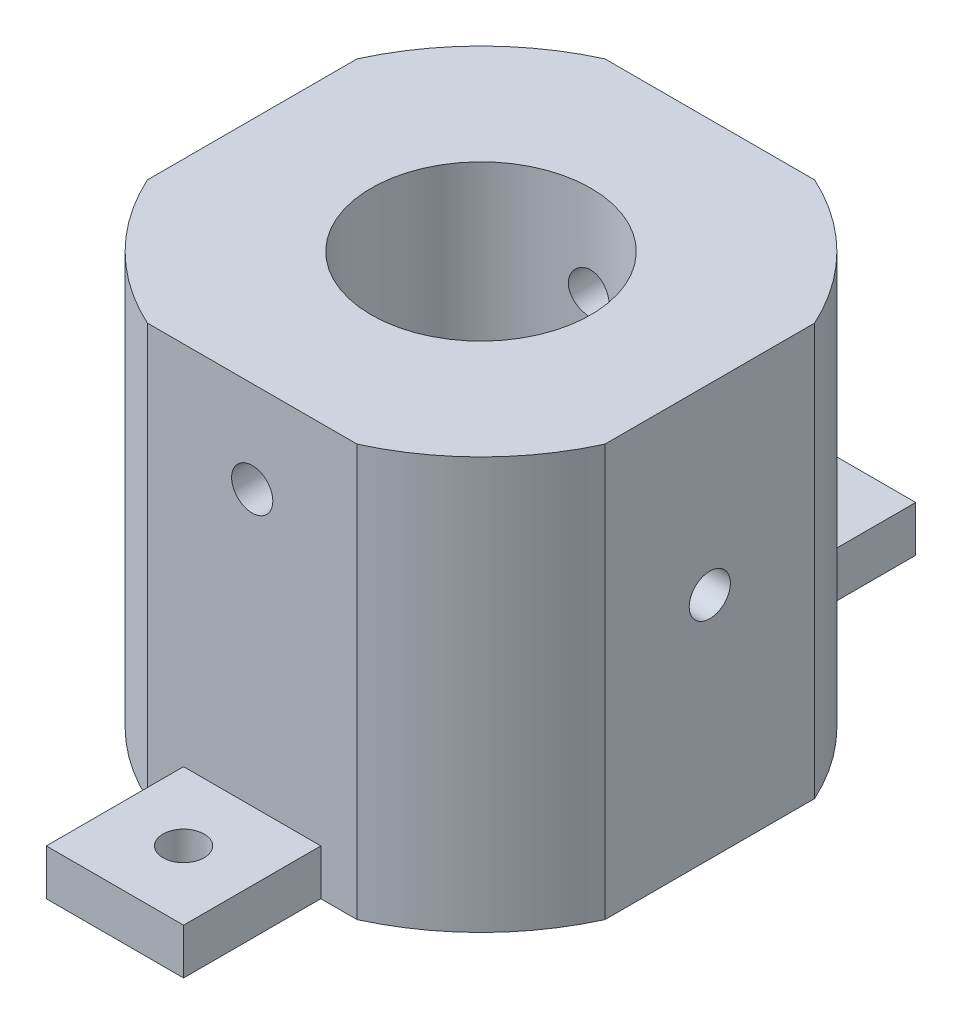
SolidWorks part; units mm, degrees
ref_plane "Ön Düzlem" through (0, 0, 0) normal (0, 0, 1) x (1, 0, 0)
ref_plane "Üst Düzlem" through (0, 0, 0) normal (0, 1, 0) x (1, 0, 0)
ref_plane "Sağ Düzlem" through (0, 0, 0) normal (1, 0, 0) x (0, 0, -1)
ref_plane "Plane1" through (0, 0, 0) normal (0, -1, 0) x (1, 0, 0)
sketch "Sketch1" plane through (0, 0, 0) normal (0, -1, 0) x (1, 0, 0)
  line L0 (-11.4564, -25) -> (11.4564, -25)
  line L1 (25, -11.4564) -> (25, 11.4564)
  line L2 (11.4564, 25) -> (-11.4564, 25)
  line L3 (-25, 11.4564) -> (-25, -11.4564)
  arc A0 (-25, -11.4564) -> (-11.4564, -25) centre (0, 0) ccw
  arc A1 (11.4564, -25) -> (25, -11.4564) centre (0, 0) ccw
  arc A2 (25, 11.4564) -> (11.4564, 25) centre (0, 0) ccw
  arc A3 (-11.4564, 25) -> (-25, 11.4564) centre (0, 0) ccw
extrude "Boss-Extrude1" add sketch "Sketch1" against normal blind 45
sketch "Sketch2" plane through (0, 0, -25) normal (0, 0, -1) x (-1, 0, 0)
  line L0 (-7.5, 5) -> (7.5, 5)
  line L1 (7.5, 5) -> (7.5, 0)
  line L2 (7.5, 0) -> (-7.5, 0)
  line L3 (-7.5, 0) -> (-7.5, 5)
extrude "Boss-Extrude2" add sketch "Sketch2" along normal blind 15
sketch "Sketch3" plane through (0, 0, 25) normal (0, 0, 1) x (1, 0, 0)
  line L0 (-7.5, 5) -> (7.5, 5)
  line L1 (7.5, 5) -> (7.5, 0)
  line L2 (7.5, 0) -> (-7.5, 0)
  line L3 (-7.5, 0) -> (-7.5, 5)
extrude "Boss-Extrude3" add sketch "Sketch3" along normal blind 15
hole_wizard "Ø24.0 (24) Diameter Hole1" positions "Sketch5" profile "Sketch4" hole size "Ø24.0" standard "ANSI Metric"
sketch "Sketch5" plane through (0, 0, 0) normal (0, -1, 0) x (-1, 0, 0)
  point P0 (0, 0)
sketch "Sketch4" plane through (0, 0, 0) normal (1, 0, 0) x (0, 0, -1)
  line L0 (0, 0) -> (0, 45)
  line L1 (0, 45) -> (12, 45)
  line L2 (12, 45) -> (12, 0)
  line L5 (12, 0) -> (0, 0)
  line L11 (0, -6.35) -> (0, 107.95) construction
  dimension "Thru Hole Dia." = 24
  dimension "Thru Hole Depth" = 45
hole_wizard "Ø4.5 (4.5) Diameter Hole1" positions "Sketch7" profile "Sketch6" hole size "Ø4.5" standard "ANSI Metric"
sketch "Sketch7" plane through (0, 0, -25) normal (0, 0, -1) x (-1, 0, 0)
  point P0 (0, 35)
sketch "Sketch6" plane through (0, 35, -25) normal (1, 0, 0) x (0, 1, 0)
  line L0 (0, 0) -> (0, 63.2128)
  line L1 (0, 63.2128) -> (2.25, 63.2128)
  line L2 (2.25, 63.2128) -> (2.25, 0)
  line L5 (2.25, 0) -> (0, 0)
  line L10 (0, 63.2128) -> (-2.25, 63.2128) construction
  line L11 (0, -6.35) -> (0, 107.95) construction
  dimension "Hole Dia." = 4.5
  dimension "Hole Depth" = 63.2128
  dimension "Drill Angle" = 180
hole_wizard "Ø4.5 (4.5) Diameter Hole2" positions "Sketch9" profile "Sketch8" hole size "Ø4.5" standard "ANSI Metric"
sketch "Sketch9" plane through (-25, 0, 0) normal (-1, 0, 0) x (0, 0, 1)
  point P0 (0, 25)
sketch "Sketch8" plane through (-25, 25, 0) normal (0, 1, 0) x (0, 0, 1)
  line L0 (0, 0) -> (0, 63.2128)
  line L1 (0, 63.2128) -> (2.25, 63.2128)
  line L2 (2.25, 63.2128) -> (2.25, 0)
  line L5 (2.25, 0) -> (0, 0)
  line L10 (0, 63.2128) -> (-2.25, 63.2128) construction
  line L11 (0, -6.35) -> (0, 107.95) construction
  dimension "Hole Dia." = 4.5
  dimension "Hole Depth" = 63.2128
  dimension "Drill Angle" = 180
hole_wizard "Ø4.5 (4.5) Diameter Hole3" positions "Sketch11" profile "Sketch10" hole size "Ø4.5" standard "ANSI Metric"
sketch "Sketch11" plane through (0, 5, 0) normal (0, 1, 0) x (1, 0, 0)
  point P0 (0, -32.5)
  point P1 (0, 32.5)
sketch "Sketch10" plane through (0, 5, 32.5) normal (1, 0, 0) x (0, 0, 1)
  line L0 (0, 0) -> (0, 5)
  line L1 (0, 5) -> (2.25, 5)
  line L2 (2.25, 5) -> (2.25, 0)
  line L5 (2.25, 0) -> (0, 0)
  line L11 (0, -6.35) -> (0, 107.95) construction
  dimension "Thru Hole Dia." = 4.5
  dimension "Thru Hole Depth" = 5
